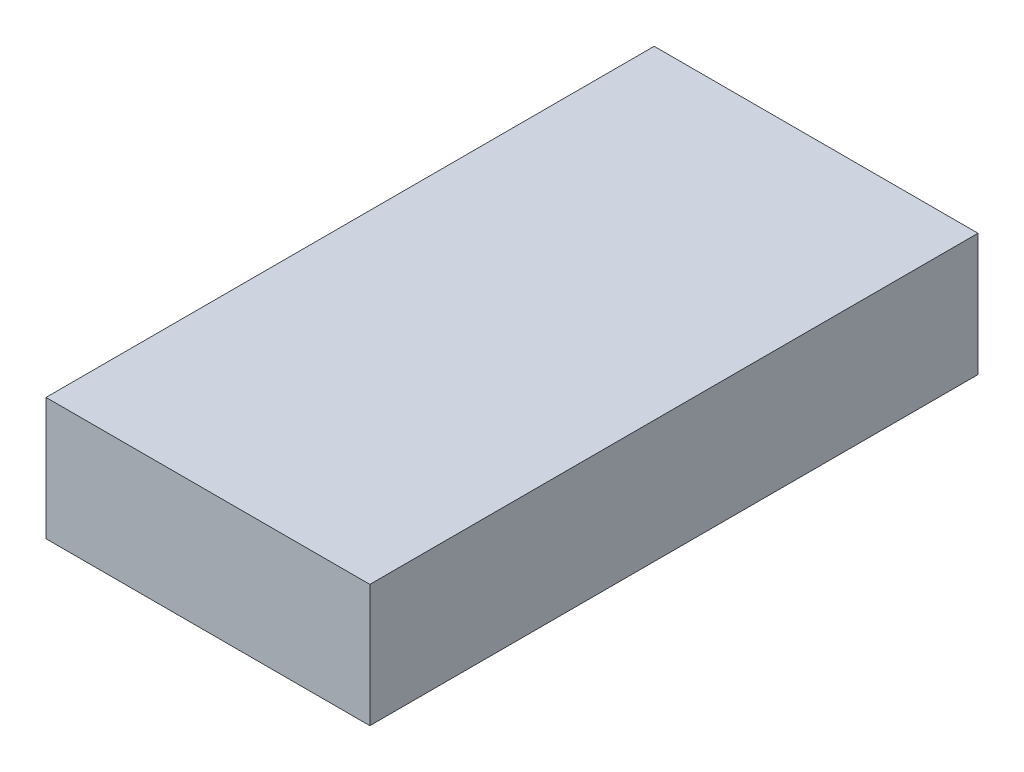
SolidWorks part; units mm, degrees
ref_plane "Front Plane" through (0, 0, 0) normal (0, 0, 1) x (1, 0, 0)
ref_plane "Top Plane" through (0, 0, 0) normal (0, 1, 0) x (1, 0, 0)
ref_plane "Right Plane" through (0, 0, 0) normal (1, 0, 0) x (0, 0, -1)
other "Center of Mass"
sketch "Sketch1" plane through (0, 0, 0) normal (1, 0, 0) x (0, 0, -1)
  line L1 (0, 0) -> (77, 0)
  line L2 (0, 0) -> (0, 15.5)
  line L3 (0, 15.5) -> (77, 15.5)
  line L4 (77, 0) -> (77, 15.5)
  dimension "D1" = 15.5
  dimension "D2" = 77
extrude "Boss-Extrude1" add sketch "Sketch1" along normal blind 41
